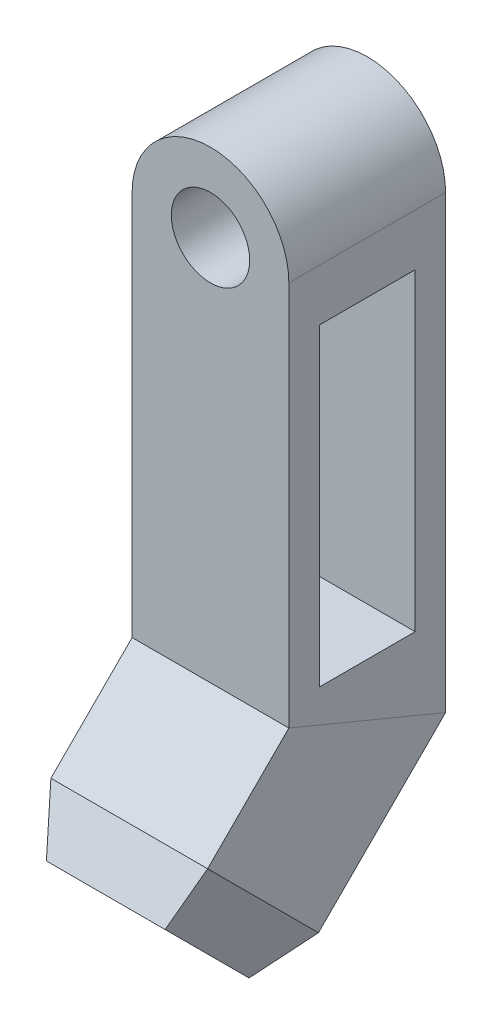
SolidWorks part; units mm, degrees
ref_plane "Front Plane" through (0, 0, 0) normal (0, 0, 1) x (1, 0, 0)
ref_plane "Top Plane" through (0, 0, 0) normal (0, 1, 0) x (1, 0, 0)
ref_plane "Right Plane" through (0, 0, 0) normal (1, 0, 0) x (0, 0, -1)
ref_plane "Plane2" through (0, 96.393, 0) normal (0, 1, 0) x (1, 0, 0)
sketch "Sketch10" plane through (0, 0, 0) normal (1, 0, 0) x (0, 0, -1)
  line L0 (0, 96.393) -> (0, -5.207)
  line L1 (55, 96.393) -> (-55, 96.393) construction
  line L2 (0, -5.207) -> (-25.3243, -30.5313)
  dimension "D1" = 101.6
  dimension "D2" = 35.814
  dimension "D3" = 135
sketch "Sketch11" plane through (0, 96.393, 0) normal (0, 1, 0) x (1, 0, 0)
  line L1 (-19.05, -19.05) -> (19.05, -19.05)
  line L2 (-19.05, -19.05) -> (-19.05, 19.05)
  line L3 (-19.05, 19.05) -> (19.05, 19.05)
  line L4 (19.05, -19.05) -> (19.05, 19.05)
  line L5 (-19.05, -19.05) -> (19.05, 19.05) construction
  line L6 (-19.05, 19.05) -> (19.05, -19.05) construction
  point P0 (0, 0)
  dimension "D1" = 38.1
sweep "Sweep1" add profiles "Sketch11" path "Sketch10"
sketch "Sketch12" plane through (0, -27.9278, 27.9278) normal (0, -0.7071, 0.7071) x (1, 0, 0)
  line L4 (19.05, -22.7319) -> (19.05, 15.3681)
  line L5 (19.05, -22.7319) -> (19.05, 15.3681)
  line L6 (19.05, 15.3681) -> (-19.05, 15.3681)
  line L7 (19.05, 15.3681) -> (-19.05, 15.3681)
  line L8 (-19.05, 15.3681) -> (-19.05, -22.7319)
  line L9 (-19.05, 15.3681) -> (-19.05, -22.7319)
  line L10 (-19.05, -22.7319) -> (19.05, -22.7319)
  line L11 (-19.05, -22.7319) -> (19.05, -22.7319)
  dimension "D1" = 0
extrude "Boss-Extrude5" add sketch "Sketch12" along normal blind 12.7 draft 20
sketch "Sketch13" plane through (0, 0, -19.05) normal (0, 0, -1) x (-1, 0, 0)
  line L0 (20.955, 96.393) -> (-20.955, 96.393) construction
  line L1 (0, 31.8146) -> (0, -31.8146) construction
  line L2 (-19.05, 96.393) -> (19.05, 96.393)
  arc A0 (19.05, 96.393) -> (-19.05, 96.393) centre (0, 96.393) ccw
  dimension "D1" = 38.1
extrude "Boss-Extrude6" add sketch "Sketch13" against normal up to surface (38.1 mm away) up to face at (0, 49.5384, 19.05)
sketch "Sketch14" plane through (0, 0, 19.05) normal (0, 0, 1) x (1, 0, 0)
  circle A0 centre (0, 96.393) radius 9.525
  arc A1 (19.05, 96.393) -> (-19.05, 96.393) centre (0, 96.393) ccw construction
  dimension "D1" = 19.05
extrude "Cut-Extrude2" cut sketch "Sketch14" against normal blind 38.1
sketch "Sketch15" plane through (0, -36.9081, 36.9081) normal (0, -0.7071, 0.7071) x (1, 0, 0)
  line L1 (-14.4276, 10.7457) -> (14.4276, -18.1095) construction
  line L2 (-14.4276, -18.1095) -> (14.4276, 10.7457) construction
  circle A2 centre (0, -3.6819) radius 12.065
  dimension "D1" = 24.13
extrude "Cut-Extrude3" cut sketch "Sketch15" against normal blind 12.7
sketch "Sketch16" plane through (19.05, 0, 0) normal (1, 0, 0) x (0, 0, -1)
  line L0 (0, 96.393) -> (0, 0) construction
  line L1 (-19.05, 96.393) -> (19.05, 96.393) construction
  line L2 (-19.05, 49.5384) -> (19.05, 49.5384) construction
  line L3 (-19.05, 96.393) -> (-19.05, 2.6838) construction
  line L4 (19.05, 96.393) -> (19.05, -13.0978) construction
  line L5 (-11.6553, 83.82) -> (11.6553, 83.82)
  line L6 (11.6553, 83.82) -> (11.6553, 7.62)
  line L7 (11.6553, 7.62) -> (-11.6553, 7.62)
  line L8 (-11.6553, 7.62) -> (-11.6553, 83.82)
  point P13 (0, 83.82)
  dimension "D1" = 90
  dimension "D2" = 90
  dimension "D3" = 90
  dimension "D4" = 90
  dimension "D5" = 76.2
  dimension "D6" = 23.3106
  dimension "D7" = 23.3106
  dimension "D8" = 83.82
extrude "Cut-Extrude4" cut sketch "Sketch16" against normal blind 59.8307
